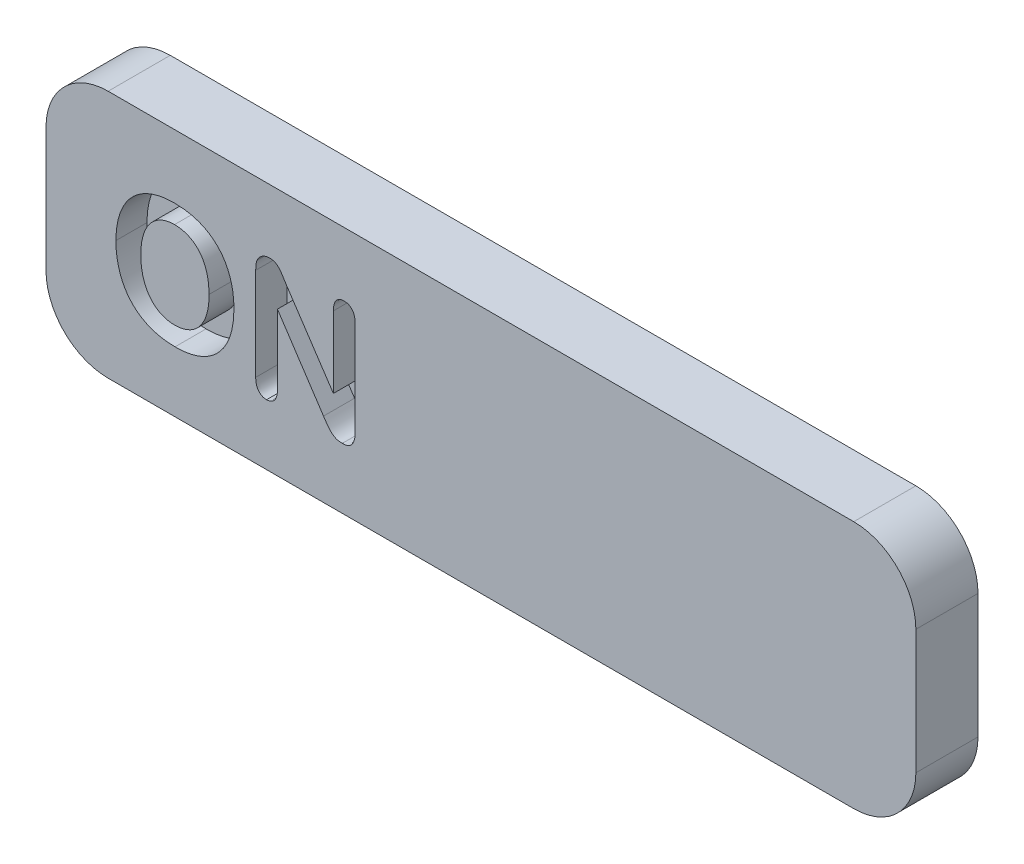
SolidWorks part; units mm, degrees
material "Benutzerdefinierter Kunststoff"
ref_plane "Ebene vorne" through (0, 0, 0) normal (0, 0, 1) x (1, 0, 0)
ref_plane "Ebene oben" through (0, 0, 0) normal (0, 1, 0) x (1, 0, 0)
ref_plane "Ebene rechts" through (0, 0, 0) normal (1, 0, 0) x (0, 0, -1)
sketch "Skizze1" plane through (0, 0, 0) normal (0, 0, 1) x (1, 0, 0)
  line L1 (1, 0) -> (13, 0)
  line L2 (0, 1) -> (0, 3)
  line L3 (1, 4) -> (13, 4)
  line L4 (14, 1) -> (14, 3)
  arc A0 (1, 0) -> (0, 1) centre (1, 1) cw
  arc A1 (0, 3) -> (1, 4) centre (1, 3) cw
  arc A2 (13, 4) -> (14, 3) centre (13, 3) cw
  arc A3 (14, 1) -> (13, 0) centre (13, 1) cw
  point P7 (0, 0)
  point P10 (0, 4)
  point P15 (14, 0)
  dimension "D3" = 1
  dimension "D1" = 14
  dimension "D2" = 4
extrude "Aufsatz-Linear austragen1" add sketch "Skizze1" along normal blind 1
sketch "Skizze2" plane through (0, 0, 1) normal (0, 0, 1) x (1, 0, 0)
  line L0 (1, 0) -> (13, 0) construction
  line L2 (0, 3) -> (0, 1) construction
  text T0 "ON" font "Arial Rounded MT Bold" height 2
  point P5 (0, 3.088)
  point P6 (0, 0)
  dimension "D1" = 1
  dimension "D2" = 1
extrude "Schnitt-Linear austragen1" cut sketch "Skizze2" against normal blind 0.5
